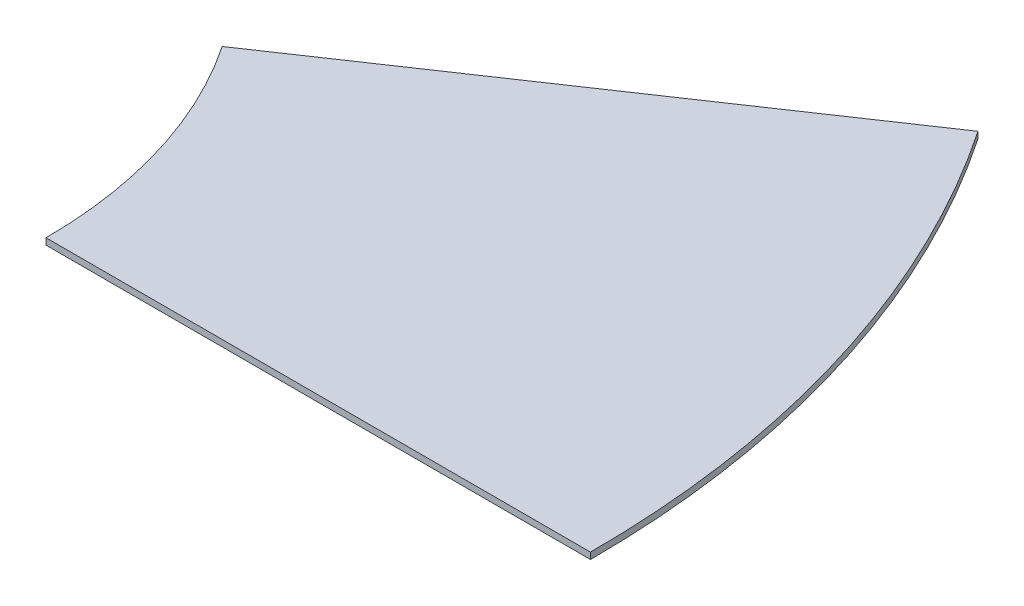
SolidWorks part; units mm, degrees
ref_plane "Front" through (0, 0, 0) normal (0, 0, 1) x (1, 0, 0)
ref_plane "Top" through (0, 0, 0) normal (0, 1, 0) x (1, 0, 0)
ref_plane "Right" through (0, 0, 0) normal (1, 0, 0) x (0, 0, -1)
sketch "草图1" plane through (0, 0, 0) normal (0, 1, 0) x (1, 0, 0)
  line L0 (0, 0) -> (110, 0) construction
  line L1 (91.1941, 61.5112) -> (0, 0) construction
  line L2 (91.1941, 61.5112) -> (41.4519, 27.9596)
  line L3 (110, 0) -> (50, 0)
  arc A0 (110, 0) -> (91.1941, 61.5112) centre (0, 0) ccw
  arc A1 (50, 0) -> (41.4519, 27.9596) centre (0, 0) ccw
  dimension "D2" = 50
  dimension "D3" = 110
  dimension "D1" = 34
extrude "凸台-拉伸1" add sketch "草图1" along normal blind 0.71 contours L3 A1 L2 A0
